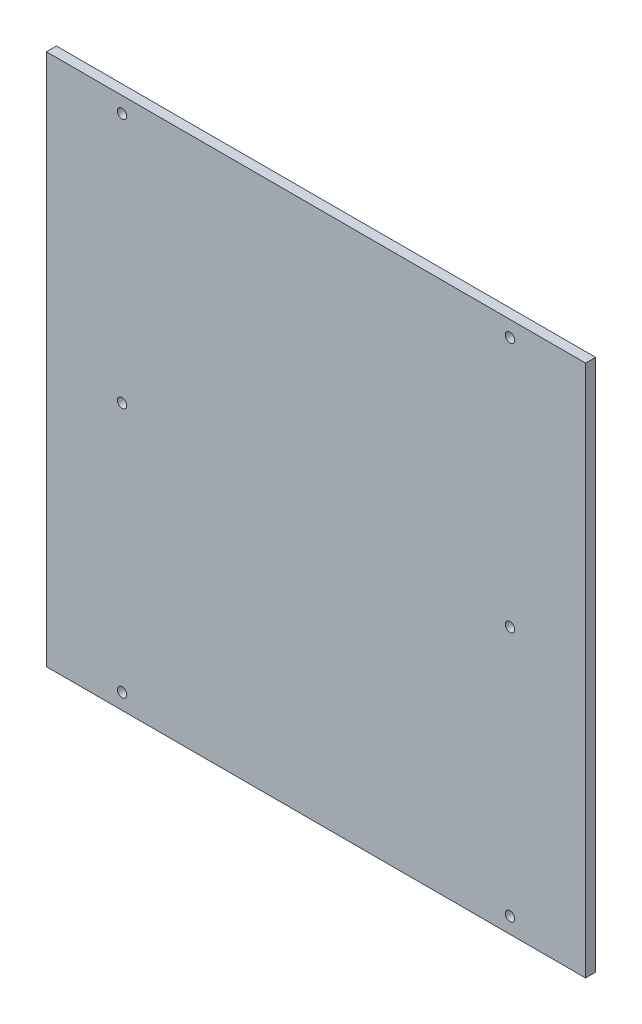
SolidWorks part; units mm, degrees
material "Acrylic (Medium-high impact)"
ref_plane "Front Plane" through (0, 0, 0) normal (0, 0, 1) x (1, 0, 0)
ref_plane "Top Plane" through (0, 0, 0) normal (0, 1, 0) x (1, 0, 0)
ref_plane "Right Plane" through (0, 0, 0) normal (1, 0, 0) x (0, 0, -1)
sketch "Sketch1" plane through (0, 0, 0) normal (0, 0, 1) x (1, 0, 0)
  line L0 (0, 0) -> (0, 169.3333)
  line L1 (0, 169.3333) -> (133.35, 169.3333)
  line L2 (133.35, 169.3333) -> (133.35, 0)
  line L3 (133.35, 0) -> (0, 0)
  line L8 (66.675, 169.3333) -> (66.675, 0) construction
  line L9 (0, 84.6667) -> (133.35, 84.6667) construction
  circle A0 centre (5, 5) radius 1.5
  circle A1 centre (5, 164.3333) radius 1.5
  circle A4 centre (5, 84.6667) radius 1.5
  circle A5 centre (128.35, 164.3333) radius 1.5
  circle A6 centre (128.35, 84.6667) radius 1.5
  circle A7 centre (128.35, 5) radius 1.5
  dimension "D7" = 3
  dimension "D10" = 3
  dimension "D1" = 169.3333
  dimension "D2" = 133.35
  dimension "D8" = 5
  dimension "D9" = 5
extrude "Boss-Extrude1" add sketch "Sketch1" along normal blind 3.175
sketch "Sketch2" [suppressed] plane through (0, 0, 3.175) normal (0, 0, 1) x (1, 0, 0)
  line L0 (10, 10) -> (10, 159.3333)
  line L1 (10, 159.3333) -> (123.35, 159.3333)
  line L2 (123.35, 159.3333) -> (123.35, 10)
  line L3 (123.35, 10) -> (10, 10)
  line L4 (0, 0) -> (133.35, 0) construction
  line L5 (0, 169.3333) -> (0, 0) construction
  line L6 (133.35, 0) -> (133.35, 169.3333) construction
  line L7 (133.35, 169.3333) -> (0, 169.3333) construction
  dimension "D1" = 10
  dimension "D2" = 10
  dimension "D3" = 10
  dimension "D4" = 127
extrude "Cut-Extrude1" [suppressed] cut sketch "Sketch2" against normal up to surface (3.175 mm away)
sketch "Sketch3" plane through (0, 0, 3.175) normal (0, 0, 1) x (1, 0, 0)
  line L0 (66.675, 0) -> (66.675, 169.3333) construction
  line L1 (0, 0) -> (133.35, 0) construction
  line L2 (133.35, 169.3333) -> (0, 169.3333) construction
  line L3 (0, 169.3333) -> (-19.05, 169.3333)
  line L4 (-19.05, 169.3333) -> (-19.05, 0)
  line L5 (-19.05, 0) -> (0, 0)
  line L6 (0, 0) -> (0, 169.3333)
  line L7 (152.4, 0) -> (133.35, 0)
  line L8 (152.4, 169.3333) -> (152.4, 0)
  line L9 (133.35, 169.3333) -> (152.4, 169.3333)
  line L10 (133.35, 0) -> (133.35, 169.3333)
  dimension "D1" = 171.45
extrude "Boss-Extrude2" add sketch "Sketch3" against normal up to surface (3.175 mm away) up to face at (126.85, 84.6667, 0)
equation "\"D1@Sketch1\"  = 254.00* (2/3)"
